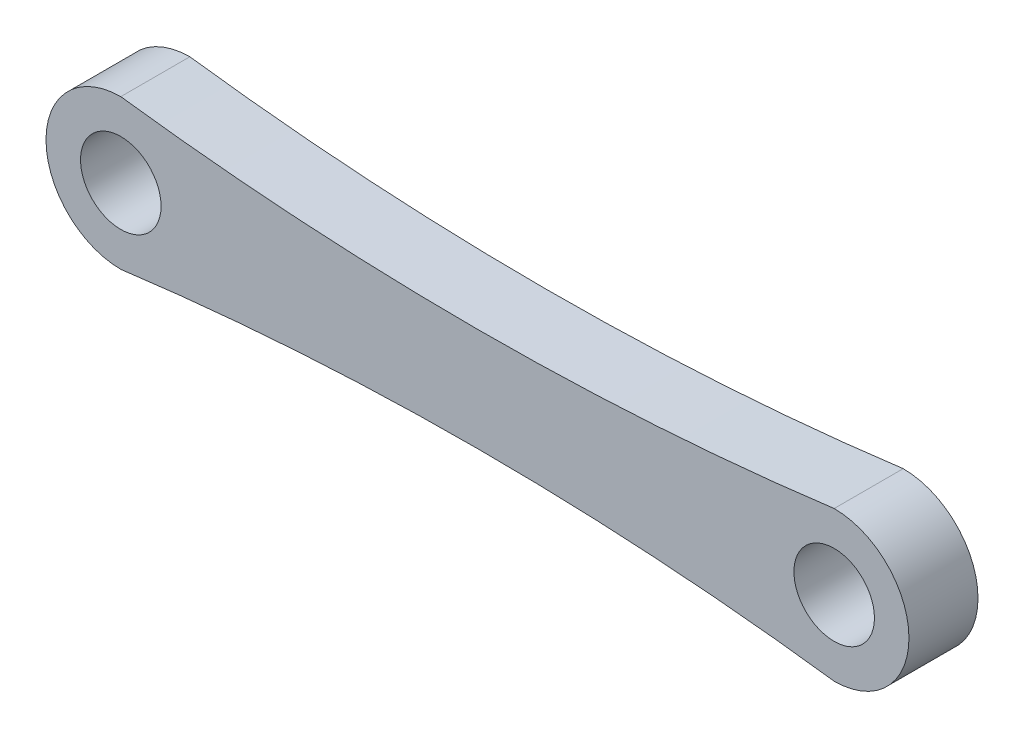
SolidWorks part; units mm, degrees
ref_plane "Front Plane" through (0, 0, 0) normal (0, 0, 1) x (1, 0, 0)
ref_plane "Top Plane" through (0, 0, 0) normal (0, 1, 0) x (1, 0, 0)
ref_plane "Right Plane" through (0, 0, 0) normal (1, 0, 0) x (0, 0, -1)
sketch "Sketch1" plane through (0, 0, 0) normal (0, 0, 1) x (1, 0, 0)
  line L0 (0, 2.8755) -> (0, -3.1126) construction
  line L1 (-4.7404, 0) -> (5.8425, 0) construction
  circle A0 centre (-15.5, 0) radius 1.75
  arc A1 (-14.6889, 3.1472) -> (-14.6889, -3.1472) centre (-15.5, 0) ccw
  arc A2 (14.6889, 3.1472) -> (14.6889, -3.1472) centre (15.5, 0) cw
  circle A3 centre (15.5, 0) radius 1.75
  arc A4 (-15.5, 3.25) -> (15.5, 3.25) centre (0, 122.2447) ccw
  arc A5 (-15.5, -3.25) -> (15.5, -3.25) centre (0, -122.2447) cw
  dimension "D1" = 3.5
  dimension "D2" = 6.5
  dimension "D4" = 120
  dimension "D3" = 31
extrude "Boss-Extrude1" add sketch "Sketch1" against normal blind 3 contours A1 A5 A2 A4 A3 A0
